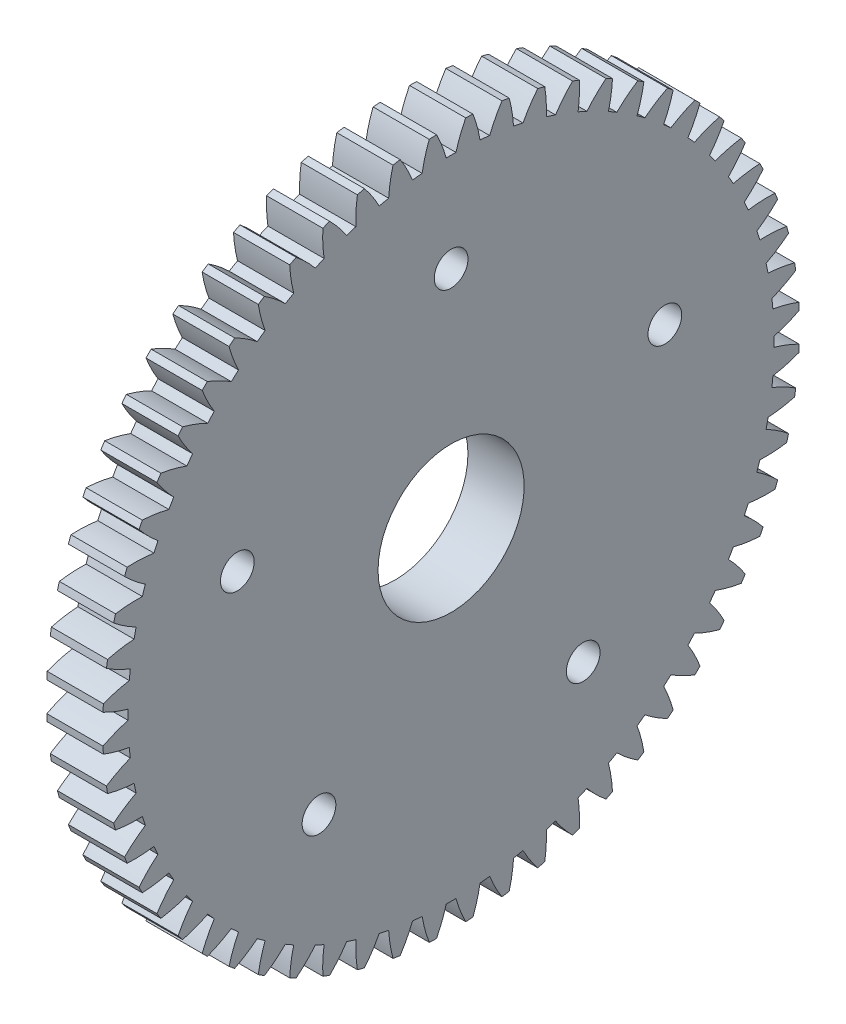
SolidWorks part; units mm, degrees
ref_plane "Plane1" through (0, 0, 0) normal (0, 0, 1) x (1, 0, 0)
ref_plane "Plane2" through (0, 0, 0) normal (0, 1, 0) x (1, 0, 0)
ref_plane "Plane3" through (0, 0, 0) normal (1, 0, 0) x (0, 0, -1)
sketch "HoldingSke" plane through (0, 0, 0) normal (0, 1, 0) x (1, 0, 0)
  line L0 (0, 0) -> (0.5, -0.866)
  line L1 (-15, 0) -> (100, 0) construction
  line L2 (0, 0) -> (-2.1039, 2.3779)
  line L3 (0, 0) -> (-11.863, 4.5341)
  line L4 (0, 0) -> (4.318, 7.479)
  line L5 (0, 0) -> (-46.8476, -17.4728)
  line L6 (0, 0) -> (-4.1448, -2.7965)
  line L7 (-2.1039, 2.3779) -> (8.6586, 51.2059)
  line L8 (-76.2, 54.61) -> (-75.7, 54.61)
  line L9 (-71.009, 38.7566) -> (-53.1078, 45.2721)
  line L10 (-76.2, 71.12) -> (104.1128, 71.12)
  line L11 (0, 0) -> (-5, 0)
  line L12 (-76.2, 101.6) -> (-76.162, 101.6)
  line L13 (24.9733, 27.94) -> (52.9518, 28.4284)
  line L14 (24.9733, 27.94) -> (24.9743, 27.94)
  line L15 (24.9733, 27.94) -> (100.4006, 29.5858)
  line L16 (-63.627, -1) -> (-12.827, -1)
  circle A0 centre (0, 0) radius 1.5
  circle A1 centre (0, 0) radius 28.749
  circle A2 centre (0, 0) radius 37.5
  circle A3 centre (0, 0) radius 1.5
  dimension "MHD" = 57.498
  dimension "Hub_dia" = 75
  dimension "Bore" = 3
  dimension "MBD" = 3
  dimension "Num_teeth" = 60
  dimension "Pitch" = 1
  dimension "Overall_len" = 50
  dimension "Show_teeth" = 60
  dimension "Thickness" = 5
  dimension "OAL" = 50.0001
  dimension "T_dim" = 0.5
  dimension "Ap" = 20
  dimension "H" = 19.05
  dimension "Pitch_radius" = 180.3128
  dimension "Width" = 5
  dimension "Backlash" = 0.038
  dimension "Addendum_fac" = 1
  dimension "Dedendum_fac" = 1.25
  dimension "Clearance_fac" = 0.25
  dimension "Dedendum_add" = 0.001
  dimension "Module" = 1
sketch "BasProSke" plane through (0, 0, 0) normal (0, 1, 0) x (1, 0, 0)
  line L0 (-10, 0) -> (60, 0) construction
  line L1 (0, 0) -> (0, 31)
  line L2 (0, 0) -> (5, 0)
  line L3 (5, 0) -> (5, 31)
  line L4 (5, 31) -> (0, 31)
  dimension "Thickness" = 5
  dimension "Diameter" = 62
revolve "Base-Revolve" add sketch "BasProSke" angle 360 about L0
sketch "TooCutSke" plane through (0, 0, 0) normal (1, 0, 0) x (0, 0, -1)
  line L1 (0, 0) -> (0, 107) construction
  line L2 (0, 0) -> (-0.8518, 29.9879) construction
  line L3 (0, 0) -> (-3.1393, 59.9006) construction
  line L4 (-0.8518, 29.9879) -> (-1.5696, 29.9503) construction
  arc A0 (0.4302, 28.7458) -> (-0.4302, 28.7458) centre (0, 0) ccw
  arc A1 (1.3127, 30.9976) -> (-1.3127, 30.9976) centre (0, 0) ccw
  circle A2 centre (0, 0) radius 30 construction
  circle A3 centre (0, 0) radius 28.1908 construction
  arc A4 (-0.4302, 28.7458) -> (-1.3127, 30.9976) centre (-11.9871, 25.5153) ccw
  arc A5 (1.3127, 30.9976) -> (0.4302, 28.7458) centre (11.9871, 25.5153) ccw
  dimension "Root_dia" = 57.498
  dimension "Overcut_dia" = 62.0508
  dimension "Pitch_dia" = 60
  dimension "Base_dia" = 56.3816
  dimension "Flank_rad" = 12
  dimension "Half_ang" = 3
  dimension "Half_CT" = 0.7188
extrude "ToothCut" cut sketch "TooCutSke" along normal through all
fillet "Breaks" [suppressed] radius 0.02
fillet "RootFillets" [suppressed] radius 0.251
pattern_circular "TeethCuts" count 60 over 360 about axis through (0, 0, 0) along (1, 0, 0) of "ToothCut", "RootFillets", "Breaks"
sketch "HubNeaOneSke" plane through (0, 0, 0) normal (-1, 0, 0) x (0, 0, 1)
  circle A0 centre (0, 0) radius 28.749
  dimension "Diameter" = 57.498
extrude "HubNearOne" [suppressed] add sketch "HubNeaOneSke" along normal blind 45.0001
sketch "HubNeaBotSke" plane through (0, 0, 0) normal (-1, 0, 0) x (0, 0, 1)
  circle A0 centre (0, 0) radius 28.749
  dimension "Diameter" = 57.498
extrude "HubNearBoth" [suppressed] add sketch "HubNeaBotSke" along normal blind 22.5
ref_plane "FarPln" through (5, 0, 0) normal (1, 0, 0) x (0, 0, -1)
sketch "HubFarSke" plane through (5, 0, 0) normal (1, 0, 0) x (0, 0, -1)
  circle A0 centre (0, 0) radius 28.749
  dimension "Diameter" = 57.498
extrude "HubFar" [suppressed] add sketch "HubFarSke" along normal blind 22.5
sketch "BorSke" plane through (0, 0, 0) normal (1, 0, 0) x (0, 0, -1)
  circle A0 centre (0, 0) radius 6.5
  dimension "Diameter" = 13
extrude "Bore" cut sketch "BorSke" along normal mid plane 100.0001
sketch "KeySke" plane through (0, 0, 0) normal (1, 0, 0) x (0, 0, -1)
  line L0 (-0.6, 0) -> (-0.6, 2)
  line L1 (-0.6, 2) -> (0.6, 2)
  line L2 (0.6, 2) -> (0.6, 0)
  line L3 (0, 0) -> (0, 34) construction
  line L4 (-0.6, 0) -> (0.6, 0)
  dimension "Offset" = 2
  dimension "Width" = 1.2
extrude "Keyway" [suppressed] cut sketch "KeySke" along normal mid plane 100.0001
sketch "草图1" plane through (5, 0, 0) normal (1, 0, 0) x (0, 0, -1)
  circle A0 centre (0, 20) radius 1.5
  circle A1 centre (0, 0) radius 6.5 construction
  circle A2 centre (19.0211, 6.1803) radius 1.5
  circle A3 centre (11.7557, -16.1803) radius 1.5
  circle A4 centre (-11.7557, -16.1803) radius 1.5
  circle A5 centre (-19.0211, 6.1803) radius 1.5
  point P14 (0, 0)
  dimension "D1" = 3
  dimension "D2" = 20
  dimension "D3" = 5
extrude "切除-拉伸2" cut sketch "草图1" against normal blind 5
equation "' \"Module@HoldingSke\" = 6.35"
equation "' \"Num_teeth@HoldingSke\" = 12"
equation "' \"Ap@HoldingSke\" =  20"
equation "' \"Ap@HoldingSke\" = 20"
equation "' \"Width@HoldingSke\" = 0.5 * 25.4"
equation "' \"Hub_dia@HoldingSke\"= 1 * 25.4"
equation "' \"Hub_dia@HoldingSke\" = 1 * 25.4"
equation "' \"Overall_len@HoldingSke\" = 1.0 * 25.4"
equation "' \"Bore@HoldingSke\" = 0.75 * 25.4"
equation "' \"T_dim@HoldingSke\" = 0.1 * 25.4"
equation "' \"Width@KeySke\" = 0.25 * 25.4"
equation "' \"Show_teeth@HoldingSke\" = 13"
equation "' \"Backlash@HoldingSke\" = 0.009 * 25.4"
equation "' \"Addendum_fac@HoldingSke\" = 1.0"
equation "' \"Dedendum_fac@HoldingSke\" = 1.25"
equation "' \"Dedendum_add@HoldingSke\" = 0.00005 * 25.4"
equation "' \"Clearance_fac@HoldingSke\" = 0.25"
equation "\"Pitch@HoldingSke\" = 1 / \"Module@HoldingSke\""
equation "\"Overcut_dia@TooCutSke\" = (\"Num_teeth@HoldingSke\" + 2 * \"Addendum_fac@HoldingSke\") / \"Pitch@HoldingSke\" + 0.002 * 25.4"
equation "\"Pitch_dia@TooCutSke\" = \"Num_teeth@HoldingSke\" / \"Pitch@HoldingSke\""
equation "\"Base_dia@TooCutSke\" = \"Num_teeth@HoldingSke\" / \"Pitch@HoldingSke\" * cos((\"Ap@HoldingSke\"  * 3.14159265 / 180))"
equation "\"Root_dia@TooCutSke\" = (\"Num_teeth@HoldingSke\" + 2) / \"Pitch@HoldingSke\" - 2 * (\"Addendum_fac@HoldingSke\" + \"Dedendum_fac@HoldingSke\") / \"Pitch@HoldingSke\" - \"Dedendum_add@HoldingSke\" * 2"
equation "\"Half_ang@TooCutSke\" = 180 / \"Num_teeth@HoldingSke\""
equation "\"Half_CT@TooCutSke\" = \"Num_teeth@HoldingSke\" / \"Pitch@HoldingSke\" * sin((3.14159265 / 2 / \"Num_teeth@HoldingSke\")) / 2 - 7 * \"Backlash@HoldingSke\" / 4"
equation "\"Flank_rad@TooCutSke\" = \"Num_teeth@HoldingSke\" / \"Pitch@HoldingSke\" / 5"
equation "\"Radius@RootFillets\" = \"Clearance_fac@HoldingSke\" / \"Pitch@HoldingSke\" + \"Dedendum_add@HoldingSke\""
equation "\"Break_rad@Breaks\" = 0.02 / \"Pitch@HoldingSke\""
equation "\"Thickness@HoldingSke\" = \"Width@HoldingSke\""
equation "\"OAL@HoldingSke\" = \"Thickness@HoldingSke\""
equation "\"MHD@HoldingSke\" = (\"Num_teeth@HoldingSke\" + 2) / \"Pitch@HoldingSke\" - 2 * (\"Addendum_fac@HoldingSke\" + \"Dedendum_fac@HoldingSke\")  / \"Pitch@HoldingSke\" - \"Dedendum_add@HoldingSke\" * 2"
equation "\"MBD@HoldingSke\" = (\"Num_teeth@HoldingSke\" + 2) / \"Pitch@HoldingSke\" - 2 * (\"Addendum_fac@HoldingSke\" + \"Dedendum_fac@HoldingSke\")  / \"Pitch@HoldingSke\" - \"Dedendum_add@HoldingSke\" * 2 - 0.002 * 25.4"
equation "\"MHD@HoldingSke\" = ((sgn( \"MHD@HoldingSke\" - \"Hub_dia@HoldingSke\" )-1)*( \"MHD@HoldingSke\" - \"Hub_dia@HoldingSke\" ))/-2+ \"Hub_dia@HoldingSke\""
equation "\"MBD@HoldingSke\" = ((sgn( \"MBD@HoldingSke\" - \"Bore@HoldingSke\" )-1)*( \"MBD@HoldingSke\" - \"Bore@HoldingSke\" ))/-2+ \"Bore@HoldingSke\""
equation "\"OAL@HoldingSke\" = ((sgn( \"OAL@HoldingSke\" - \"Overall_len@HoldingSke\" )+1)*( \"OAL@HoldingSke\" - \"Overall_len@HoldingSke\" ))/2 + \"Overall_len@HoldingSke\" + 0.000002 * 25.4"
equation "\"Num_teeth@TeethCuts\" = int( \"Show_teeth@HoldingSke\" ) + 1"
equation "\"Num_teeth@TeethCuts\" = ((sgn( \"Num_teeth@TeethCuts\" - \"Num_teeth@HoldingSke\" )-1)*( \"Num_teeth@TeethCuts\" - \"Num_teeth@HoldingSke\" ))/-2+ \"Num_teeth@HoldingSke\""
equation "\"Num_teeth@TeethCuts\" = ((sgn( \"Num_teeth@TeethCuts\" - 2.0)+1)*( \"Num_teeth@TeethCuts\" - 2.0))/2 +2.0"
equation "\"Angle@TeethCuts\" = 360.0 / \"Num_teeth@HoldingSke\""
equation "\"Diameter@BasProSke\" = (\"Num_teeth@HoldingSke\" + 2 * \"Addendum_fac@HoldingSke\") / \"Pitch@HoldingSke\""
equation "\"Thickness@BasProSke\"  = \"Thickness@HoldingSke\""
equation "' \"Fillet_rad@BasProSke\" =  \"Thickness@HoldingSke\" * 0.05"
equation "' \"Fillet_rad@BasProSke\" = \"Thickness@HoldingSke\" * 0.05"
equation "\"MHD@HoldingSke\" = ((sgn( \"MHD@HoldingSke\" - \"Root_dia@TooCutSke\" )-1)*( \"MHD@HoldingSke\" - \"Root_dia@TooCutSke\" ))/-2+ \"Root_dia@TooCutSke\""
equation "\"Diameter@HubNeaOneSke\" = \"MHD@HoldingSke\""
equation "\"Length@HubNearOne\" = \"OAL@HoldingSke\" - \"Thickness@BasProSke\""
equation "\"Diameter@HubNeaBotSke\" = \"MHD@HoldingSke\""
equation "\"Length@HubNearBoth\" = ( \"OAL@HoldingSke\" - \"Thickness@BasProSke\" ) / 2.0"
equation "\"Thickness@FarPln\" = \"Thickness@BasProSke\""
equation "\"Diameter@HubFarSke\" = \"MHD@HoldingSke\""
equation "\"Length@HubFar\" = ( \"OAL@HoldingSke\" - \"Thickness@BasProSke\" ) / 2.0"
equation "\"D1@Bore\" = \"OAL@HoldingSke\" * 2.0"
equation "\"D1@Keyway\" = \"OAL@HoldingSke\" * 2.0"
equation "\"Offset@KeySke\" = \"T_dim@HoldingSke\" + \"MBD@HoldingSke\" / 2.0"
